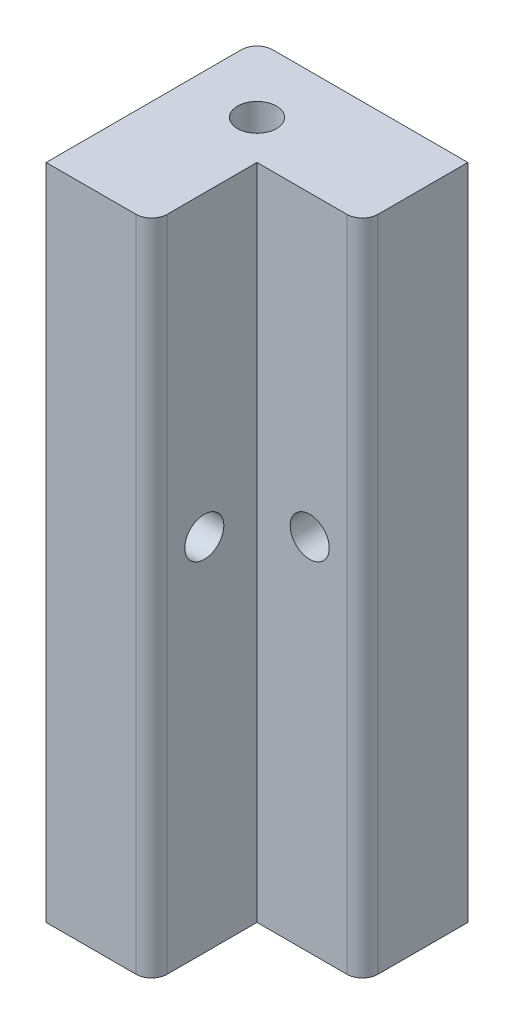
SolidWorks part; units mm, degrees
material "ABS"
ref_plane "Front Plane" through (0, 0, 0) normal (0, 0, 1) x (1, 0, 0)
ref_plane "Top Plane" through (0, 0, 0) normal (0, 1, 0) x (1, 0, 0)
ref_plane "Right Plane" through (0, 0, 0) normal (1, 0, 0) x (0, 0, -1)
sketch "Sketch4" plane through (0, 0, 0) normal (0, 1, 0) x (1, 0, 0)
  line L27 (0, 0) -> (-2.5, 0) construction
  line L55 (0, 0) -> (2.5, 0) construction
  line L56 (2.5, 0) -> (5, 0) construction
  line L61 (-2.5, 0) -> (-8.5, 0) construction
  line L62 (0, 0) -> (0, 2.5) construction
  line L63 (0, 2.5) -> (0, 8.5) construction
  line L64 (-8.5, 8.5) -> (5, 8.5)
  line L65 (5, 8.5) -> (5, -5)
  line L66 (5, -5) -> (-8.5, -5)
  line L67 (-8.5, -5) -> (-8.5, 8.5)
  line L68 (0, 0) -> (0, -2.5) construction
  line L69 (0, -2.5) -> (0, -5) construction
  circle A3 centre (0, 0) radius 2.5
  point P10 (0, 0)
  dimension "D2" = 5
  dimension "D1" = 6
  dimension "D3" = 2.5
extrude "hole-TopMain" add sketch "Sketch4" along normal up to surface (64.27 mm away)
ref_plane "Plane-Side" through (-3.5, 0, 0) normal (-1, 0, 0) x (0, 0, 1)
sketch "Sketch13" [suppressed] plane through (-3.5, 0, 0) normal (-1, 0, 0) x (0, 0, 1)
  circle A0 centre (-1.75, 46.135) radius 3.25
  circle A1 centre (-1.75, 46.135) radius 2.5 construction
  dimension "D1" = 6.5
extrude "hole-Side2" [suppressed] cut sketch "Sketch13" against normal through all
ref_plane "Plane2" through (0, 0, -3.5) normal (0, 0, -1) x (-1, 0, 0)
sketch "Sketch14" plane through (0, 0, -8.5) normal (0, 0, -1) x (-1, 0, 0)
  line L0 (1.75, 66.1204) -> (1.75, -49933.8796) construction
  line L1 (8.5, 64.27) -> (-5, 64.27) construction
  circle A0 centre (1.75, 46.135) radius 2.5
  circle A1 centre (1.75, 46.135) radius 2.5 construction
  point P2 (1.75, 64.27)
  dimension "D1" = 5
extrude "Cut-Extrude9" cut sketch "Sketch14" against normal through all
sketch "Sketch15" plane through (0, 0, -3.5) normal (0, 0, -1) x (-1, 0, 0)
  circle A0 centre (1.75, 46.135) radius 3.25
  circle A1 centre (1.75, 46.135) radius 2.5 construction
  dimension "D1" = 6.5
extrude "Cut-Extrude10" cut sketch "Sketch15" against normal through all
sketch "Sketch18" plane through (0, 0, 5) normal (0, 0, 1) x (1, 0, 0)
  line L0 (-8.5, 64.27) -> (5, 64.27)
  line L1 (5, 64.27) -> (5, 0)
  line L2 (5, 0) -> (-8.5, 0)
  line L3 (-8.5, 0) -> (-8.5, 64.27)
  circle A0 centre (-1.75, 46.135) radius 3.25
extrude "Boss-Extrude2" add sketch "Sketch18" along normal blind 13.5
fillet "Fillet3" radius 2 2 edges at (-8.5, 32.135, -8.5) (5, 32.135, 18.5)
sketch "Sketch19" plane through (-8.5, 0, 0) normal (-1, 0, 0) x (0, 0, 1)
  line L0 (18.5, 64.27) -> (18.5, 0) construction
  circle A1 centre (11.75, 46.135) radius 2.5
  dimension "D2" = 5
  dimension "D1" = 6.75
extrude "Cut-Extrude11" cut sketch "Sketch19" against normal blind 13.5
sketch "Sketch22" plane through (5, 0, 0) normal (1, 0, 0) x (0, 0, -1)
  line L0 (-16.5, 0) -> (8.5, 0) construction
  line L1 (8.5, 64.27) -> (-5, 64.27)
  line L2 (8.5, 64.27) -> (8.5, 0)
  line L3 (8.5, 0) -> (-5, 0)
  line L4 (-5, 64.27) -> (-5, 0)
  dimension "D1" = 13.5
extrude "Boss-Extrude3" add sketch "Sketch22" along normal blind 13.5
sketch "Sketch24" plane through (0, 0, 18.5) normal (0, 0, 1) x (1, 0, 0)
  circle A0 centre (-1.75, 46.135) radius 3.25
extrude "Boss-Extrude5" add sketch "Sketch24" against normal up to surface (27 mm away) up to face at (-4.25, 46.135, -8.5)
sketch "Sketch25" plane through (0, 64.27, 0) normal (0, 1, 0) x (1, 0, 0)
  circle A0 centre (0, 0) radius 2.5
extrude "Cut-Extrude12" cut sketch "Sketch25" against normal up to surface (64.27 mm away) up to face at (3.3125, 0, 5)
sketch "Sketch26" plane through (-8.5, 0, 0) normal (-1, 0, 0) x (0, 0, 1)
  circle A1 centre (11.75, 46.135) radius 2.5
extrude "Cut-Extrude13" cut sketch "Sketch26" against normal blind 13.5
sketch "Sketch28" plane through (0, 0, -8.5) normal (0, 0, -1) x (-1, 0, 0)
  line L0 (-11.75, 64.27) -> (-11.75, 46.135) construction
  line L1 (6.5, 64.27) -> (-18.5, 64.27) construction
  line L2 (8.5, 64.27) -> (8.5, 0) construction
  circle A0 centre (-11.75, 46.135) radius 2.5
  dimension "D3" = 5
  dimension "D1" = 18.135
  dimension "D2" = 20.25
extrude "Cut-Extrude14" cut sketch "Sketch28" against normal blind 13.5
fillet "Fillet4" radius 2 1 edges at (18.5, 32.135, 5)
sketch "Sketch29" plane through (0, 64.27, 0) normal (0, 1, 0) x (1, 0, 0)
  line L0 (18.5, 8.5) -> (-6.5, 8.5)
  line L1 (-6.5, 8.5) -> (-8.5, 8.5)
  line L2 (-8.5, 8.5) -> (-8.5, -18.5)
  line L3 (5, -5) -> (5, -16.5)
  line L4 (5, -16.5) -> (5, -18.5)
  line L5 (5, -18.5) -> (-8.5, -18.5)
  line L6 (5, -5) -> (18.5, -5)
  line L7 (18.5, -5) -> (18.5, -3)
  line L14 (5, -5) -> (16.5, -5)
  line L15 (18.5, -3) -> (18.5, 8.5)
  line L16 (18.5, 8.5) -> (-6.5, 8.5)
  line L17 (-8.5, 6.5) -> (-8.5, -18.5)
  line L18 (-8.5, -18.5) -> (3, -18.5)
  line L19 (5, -16.5) -> (5, -5)
  line L20 (5, -5) -> (16.5, -5)
  line L22 (18.5, 8.5) -> (-6.5, 8.5)
  line L23 (-8.5, 6.5) -> (-8.5, -18.5)
  line L24 (-8.5, -18.5) -> (3, -18.5)
  line L25 (5, -16.5) -> (5, -5)
  arc A3 (16.5, -5) -> (18.5, -3) centre (16.5, -3) ccw
  arc A4 (-6.5, 8.5) -> (-8.5, 6.5) centre (-6.5, 6.5) ccw
  arc A5 (3, -18.5) -> (5, -16.5) centre (3, -16.5) ccw
  arc A6 (16.5, -5) -> (18.5, -3) centre (16.5, -3) ccw
  arc A7 (-6.5, 8.5) -> (-8.5, 6.5) centre (-6.5, 6.5) ccw
  arc A8 (3, -18.5) -> (5, -16.5) centre (3, -16.5) ccw
  circle M10 centre (0, 0) radius 2.5
  line M11 (5, -5) -> (16.5, -5)
  arc M12 (16.5, -5) -> (18.5, -3) centre (16.5, -3) ccw
  line M13 (18.5, -3) -> (18.5, 8.5)
  line M14 (18.5, 8.5) -> (-6.5, 8.5)
  arc M15 (-6.5, 8.5) -> (-8.5, 6.5) centre (-6.5, 6.5) ccw
  line M16 (-8.5, 6.5) -> (-8.5, -18.5)
  line M17 (-8.5, -18.5) -> (3, -18.5)
  arc M18 (3, -18.5) -> (5, -16.5) centre (3, -16.5) ccw
  line M19 (5, -16.5) -> (5, -5)
  dimension "D1" = 0
extrude "Boss-Extrude6" add sketch "Sketch29" along normal blind 20 contours M19 M11 M12 M13 M14 M15 M16 M17 M18 M10
equation "\"tolerance\"= 0.1mm"
